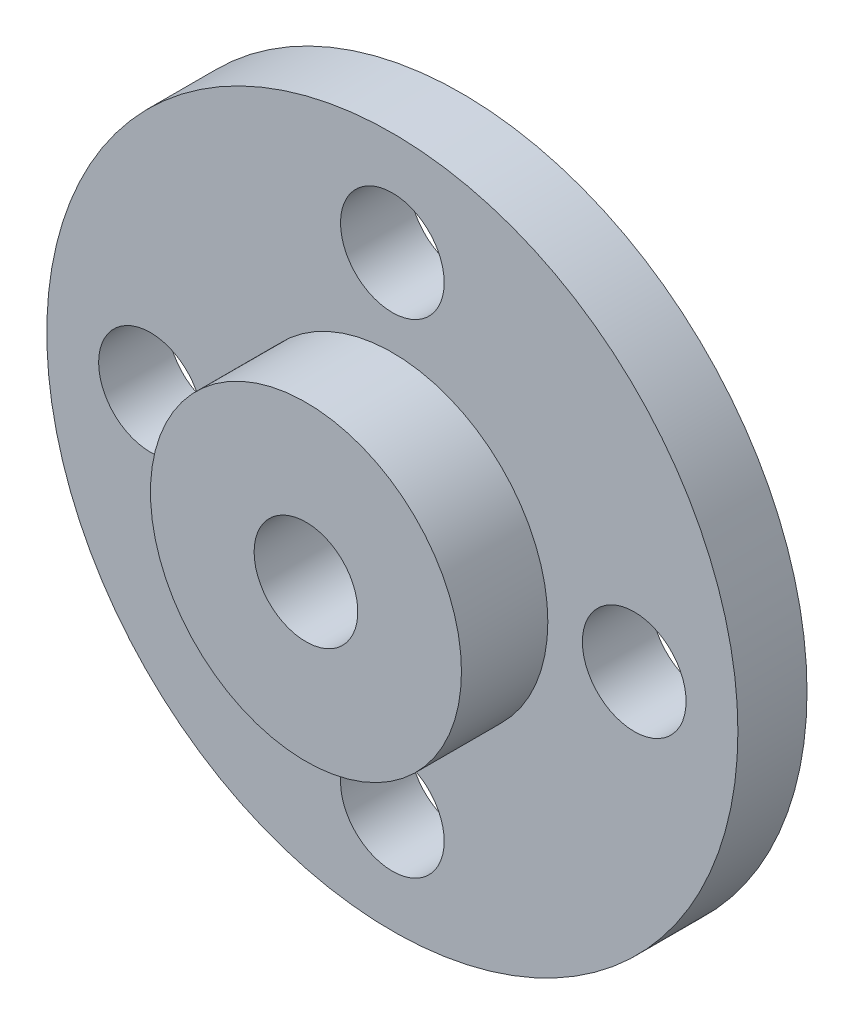
SolidWorks part; units mm, degrees
ref_plane "前视基准面" through (0, 0, 0) normal (0, 0, 1) x (1, 0, 0)
ref_plane "上视基准面" through (0, 0, 0) normal (0, 1, 0) x (1, 0, 0)
ref_plane "右视基准面" through (0, 0, 0) normal (1, 0, 0) x (0, 0, -1)
sketch "草图1" plane through (0, 0, 0) normal (0, 0, 1) x (1, 0, 0)
  circle A0 centre (0, 0) radius 10
  dimension "D1" = 20
extrude "凸台-拉伸1" add sketch "草图1" along normal blind 2
sketch "草图2" plane through (0, 0, 2) normal (0, 0, 1) x (1, 0, 0)
  circle A0 centre (0, 0) radius 4.5
  dimension "D1" = 9
extrude "凸台-拉伸2" add sketch "草图2" along normal blind 2.5
sketch "草图3" plane through (0, 0, 0) normal (0, 0, -1) x (-1, 0, 0)
  circle A0 centre (0, 7) radius 1.5
  circle A1 centre (7, 0) radius 1.5
  circle A2 centre (0, -7) radius 1.5
  circle A3 centre (-7, 0) radius 1.5
  point P12 (0, 0)
  dimension "D1" = 3
  dimension "D2" = 4
  dimension "D3" = 14
extrude "切除-拉伸1" cut sketch "草图3" against normal blind 2.5
sketch "草图4" plane through (0, 0, 0) normal (0, 0, -1) x (-1, 0, 0)
  circle A0 centre (0, 0) radius 1.5
  dimension "D1" = 3
extrude "切除-拉伸2" cut sketch "草图4" against normal through all
